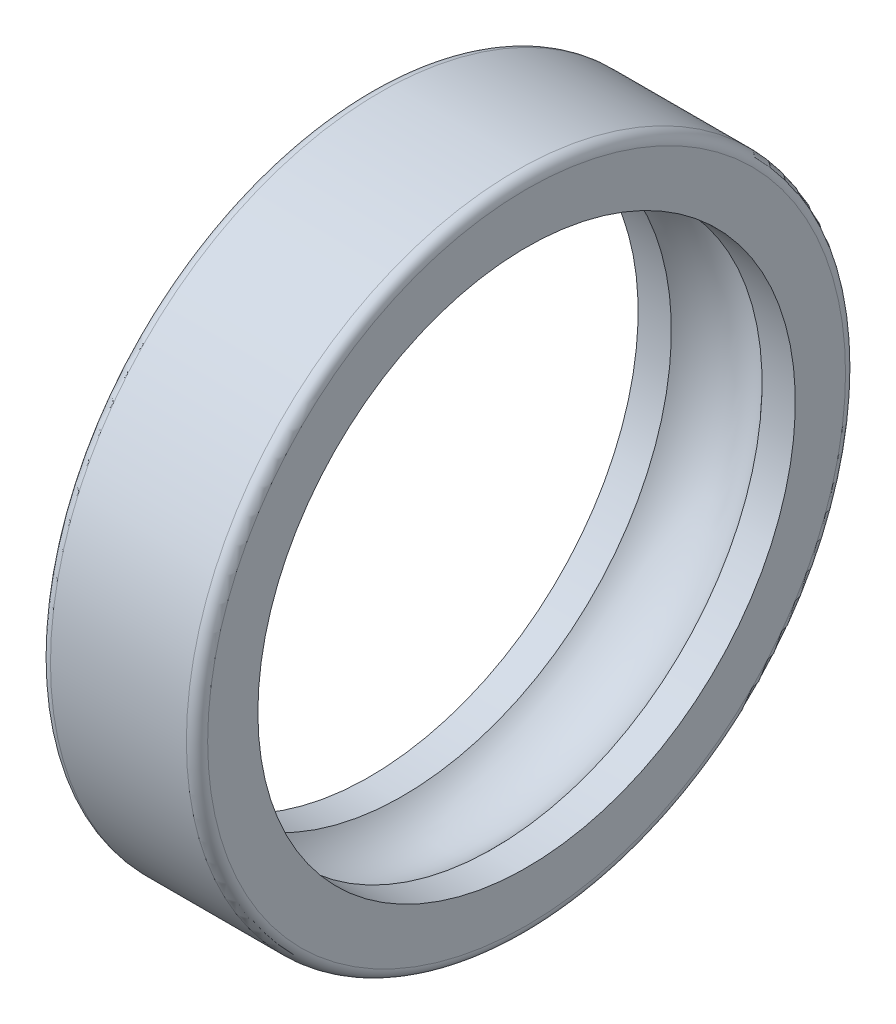
SolidWorks part; units mm, degrees
ref_plane "Front Plane" through (0, 0, 0) normal (0, 0, 1) x (1, 0, 0)
ref_plane "Top Plane" through (0, 0, 0) normal (0, 1, 0) x (1, 0, 0)
ref_plane "Right Plane" through (0, 0, 0) normal (1, 0, 0) x (0, 0, -1)
sketch "Sketch1" plane through (0, 0, 0) normal (0, 0, 1) x (1, 0, 0)
  line L0 (-28.7227, 0) -> (30.1185, 0) construction
  line L2 (-31, 65) -> (0, 65)
  line L3 (-31, 65) -> (-31, 53)
  line L4 (-31, 53) -> (-24.4443, 53)
  line L5 (0, 65) -> (0, 53)
  line L6 (-31, 65) -> (0, 53) construction
  line L7 (-31, 53) -> (0, 65) construction
  line L8 (-6.5557, 53) -> (0, 53)
  arc A0 (-6.5557, 53) -> (-24.4443, 53) centre (-15.5, 45) ccw
  point P3 (-15.5, 59)
  dimension "D5" = 12
  dimension "D1" = 31
  dimension "D2" = 53
  dimension "D3" = 65
  dimension "D4" = 8
revolve "Revolve1" add sketch "Sketch1" angle 360 about L0
fillet "Fillet1" radius 2.1 2 edges at (0, 0, 65) (-31, 0, 65)
scale "Scale1" scale about centroid uniform scaling yes scale factor 0.2
scale "Scale2" scale about centroid uniform scaling yes scale factor 1.9329
scale "Scale3" scale about centroid uniform scaling yes scale factor 1.5
